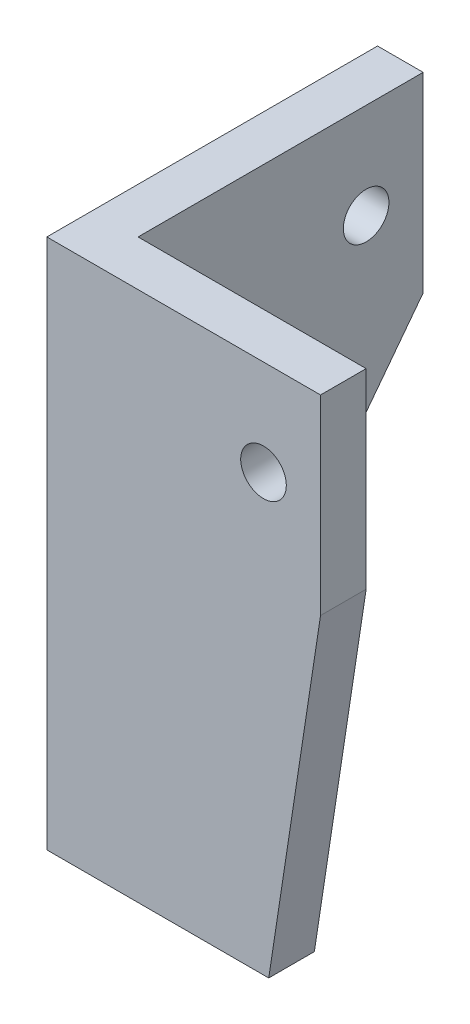
SolidWorks part; units mm, degrees
ref_plane "Front Plane" through (0, 0, 0) normal (0, 0, 1) x (1, 0, 0)
ref_plane "Top Plane" through (0, 0, 0) normal (0, 1, 0) x (1, 0, 0)
ref_plane "Right Plane" through (0, 0, 0) normal (1, 0, 0) x (0, 0, -1)
sketch "Sketch1" plane through (0, 0, 0) normal (0, 0, 1) x (1, 0, 0)
  line L0 (-92, -50.55) -> (-75, -50.55) construction
  line L4 (-90, -50.55) -> (-75, -50.55)
  line L7 (-80, -1) -> (-70, -1)
  line L9 (-80, -1) -> (-90, -1) construction
  line L12 (-80, -1) -> (-90, -1)
  line L14 (80, -1) -> (-80, -1) construction
  line L15 (-70, -1) -> (-70, -17.75)
  line L16 (-80, -17.75) -> (-21.5, -17.75) construction
  line L19 (-75, -50.55) -> (-70, -17.75)
  line L21 (-90, -17.75) -> (-90, -1) construction
  line L22 (-90, -17.75) -> (-90, -1)
  line L23 (-90, -17.75) -> (-90, -50.55)
extrude "Boss-Extrude1" add sketch "Sketch1" along normal blind 4
sketch "Sketch2" plane through (-90, 0, 0) normal (-1, 0, 0) x (0, 0, 1)
  line L2 (0, -1) -> (-25, -1)
  line L4 (0, -1) -> (0, -50.55)
  line L5 (0, -50.55) -> (4, -50.55)
  line L6 (4, -50.55) -> (4, -1)
  line L7 (4, -1) -> (0, -1)
  line L9 (0, -50.55) -> (4, -50.55)
  line L10 (4, -50.55) -> (4, -1)
  line L11 (4, -1) -> (0, -1)
  line L12 (-10, -1) -> (-222, -1) construction
  line L14 (-25, -1) -> (-25, -17.75)
  line L15 (-222, -17.75) -> (-10, -17.75) construction
  line L16 (-25, -17.75) -> (0, -50.55)
  dimension "D1" = 0
extrude "Boss-Extrude2" add sketch "Sketch2" along normal blind 4
sketch "Sketch3" plane through (0, 0, 4) normal (0, 0, 1) x (1, 0, 0)
  line L0 (-94, -50.55) -> (-94, -49.55)
  line L1 (-94, -49.55) -> (-94, -47.55)
  line L2 (-94, -47.55) -> (-74.5427, -47.55)
  line L5 (-75, -50.55) -> (-70, -17.75)
  line L6 (-70, -17.75) -> (-70, -1)
  line L7 (-70, -1) -> (-94, -1)
  line L8 (-94, -1) -> (-94, -50.55)
  line L9 (-94, -50.55) -> (-75, -50.55)
  line L10 (-75, -50.55) -> (-74.5427, -47.55)
  line L13 (-94, -47.55) -> (-94, -50.55)
  line L14 (-94, -50.55) -> (-75, -50.55)
  line M6 (-75, -50.55) -> (-70, -17.75)
  line M9 (-94, -1) -> (-94, -50.55)
  line M10 (-94, -50.55) -> (-75, -50.55)
  dimension "D1" = 0
extrude "Cut-Extrude1" cut sketch "Sketch3" against normal through all contours L2 M9 M10 M6
sketch "Sketch4" plane through (0, 0, 4) normal (0, 0, 1) x (1, 0, 0)
  circle A0 centre (-75, -9.375) radius 2
extrude "Cut-Extrude2" cut sketch "Sketch4" against normal up to surface (4 mm away) up to face at (-78.9085, -22.97, 0)
sketch "Sketch5" plane through (-94, 0, 0) normal (-1, 0, 0) x (0, 0, 1)
  line L0 (-25, -9.375) -> (-20, -9.375)
  line L1 (-25, -1) -> (-25, -17.75) construction
  circle A0 centre (-20, -9.375) radius 2
extrude "Cut-Extrude3" cut sketch "Sketch5" against normal up to surface (4 mm away) up to face at (-90, -22.97, -10.4573)
